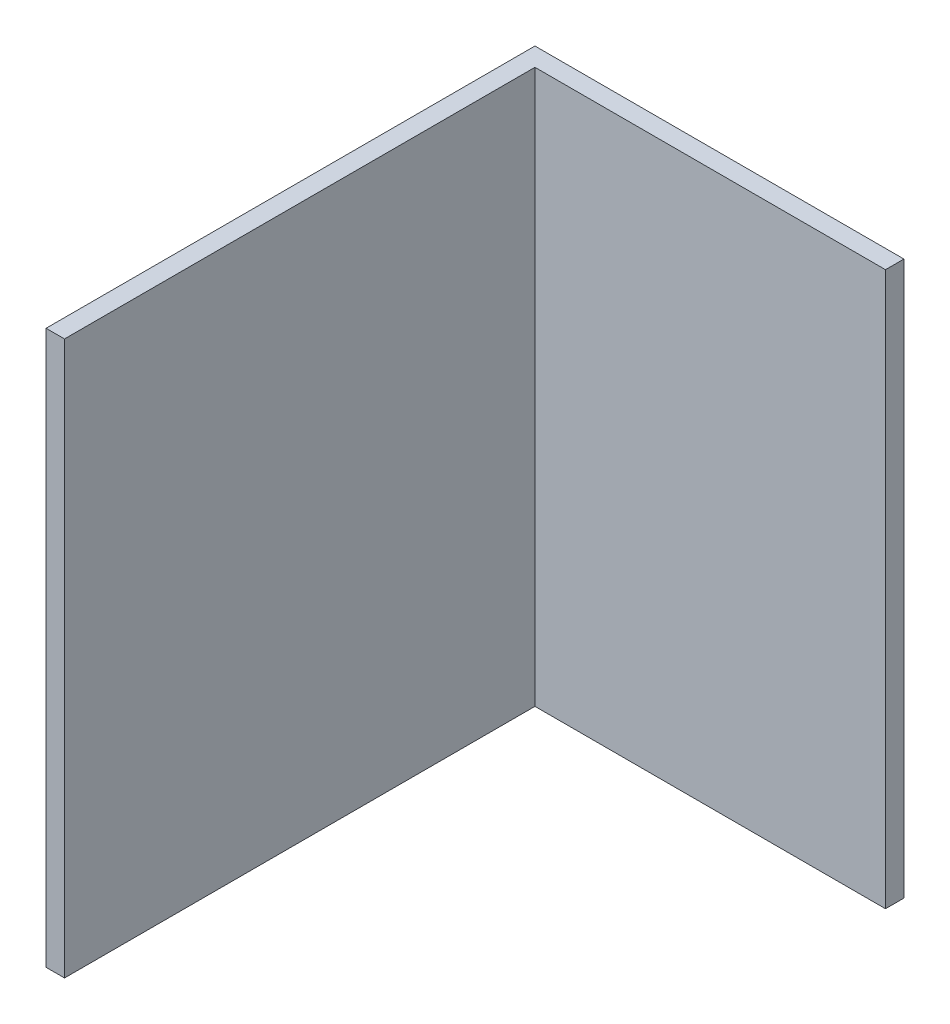
SolidWorks part; units mm, degrees
ref_plane "Front Plane" through (0, 0, 0) normal (0, 0, 1) x (1, 0, 0)
ref_plane "Top Plane" through (0, 0, 0) normal (0, 1, 0) x (1, 0, 0)
ref_plane "Right Plane" through (0, 0, 0) normal (1, 0, 0) x (0, 0, -1)
sketch "Sketch1" plane through (0, 0, 0) normal (0, 1, 0) x (1, 0, 0)
  line L0 (0, 0) -> (0, -265)
  line L1 (0, -265) -> (10, -265)
  line L2 (10, -265) -> (10, -10)
  line L3 (10, -10) -> (200, -10)
  line L4 (200, -10) -> (200, 0)
  line L5 (200, 0) -> (0, 0)
  dimension "D1" = 10
  dimension "D2" = 10
  dimension "D3" = 200
  dimension "D4" = 265
extrude "Boss-Extrude1" add sketch "Sketch1" along normal blind 300
